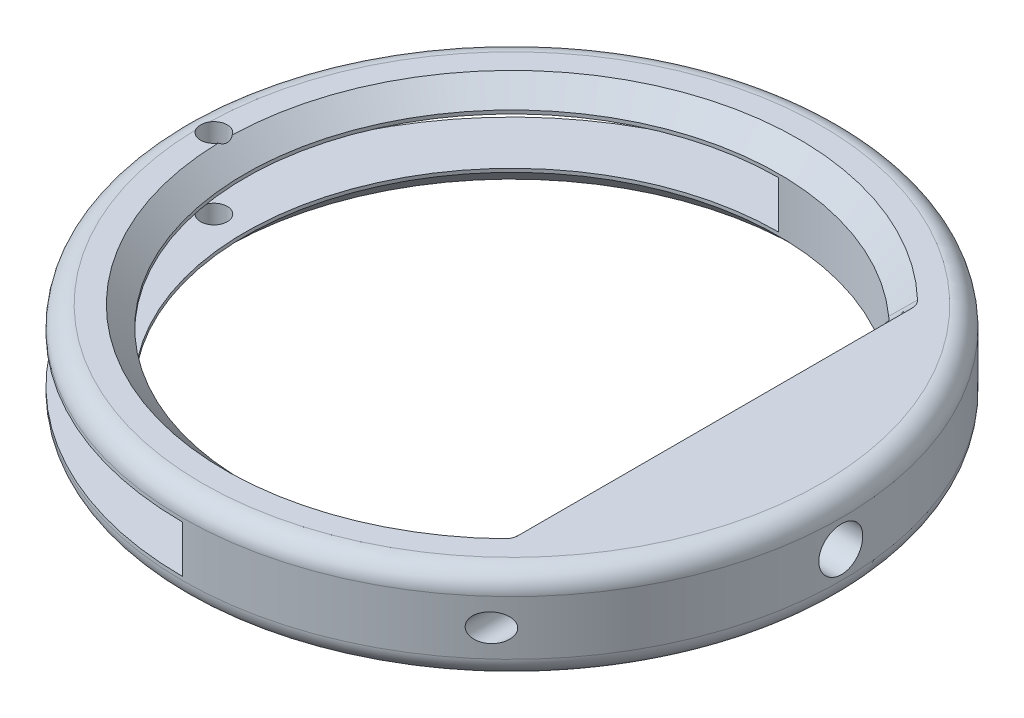
SolidWorks part; units mm, degrees
ref_plane "Front Plane" through (0, 0, 0) normal (0, 0, 1) x (1, 0, 0)
ref_plane "Top Plane" through (0, 0, 0) normal (0, 1, 0) x (1, 0, 0)
ref_plane "Right Plane" through (0, 0, 0) normal (1, 0, 0) x (0, 0, -1)
sketch "Sketch1" plane through (0, 0, 0) normal (0, 1, 0) x (1, 0, 0)
  circle A0 centre (0, 0) radius 17
  circle A1 centre (0, 0) radius 21
  dimension "D1" = 34
  dimension "D2" = 4
extrude "Boss-Extrude1" add sketch "Sketch1" along normal blind 6
sketch "Sketch2" plane through (0, 0, 0) normal (1, 0, 0) x (0, 0, -1)
  line L0 (21, 3) -> (-21, 3) construction
  line L1 (21, 0) -> (21, 6) construction
  line L2 (-21, 6) -> (-21, 0) construction
  line L4 (21, 4.5) -> (-21, 4.5)
  line L5 (21, 4.5) -> (21, 1.5)
  line L6 (21, 1.5) -> (-21, 1.5)
  line L7 (-21, 4.5) -> (-21, 1.5)
  dimension "D1" = 1.5
  dimension "D2" = 3
extrude "Cut-Extrude1" cut sketch "Sketch2" against normal blind 25.812
ref_plane "Plane1" through (17, 0, 0) normal (-1, 0, 0) x (0, 0, 1)
sketch "Sketch3" plane through (17, 0, 0) normal (-1, 0, 0) x (0, 0, 1)
  line L0 (-17, 0) -> (17, 0) construction
  line L1 (17, 0) -> (-17, 0)
  line L2 (17, 0) -> (17, 6)
  line L3 (17, 6) -> (-17, 6)
  line L4 (-17, 0) -> (-17, 6)
  line L5 (-21, 0) -> (21, 0) construction
  line L6 (17, 6) -> (-17, 6) construction
  line L7 (16.8602, 4.3201) -> (-16.6398, 4.3201) construction
  line L8 (-16.4907, 4.3201) -> (16.7109, 4.3201)
  line L9 (-16.4907, 4.3201) -> (-16.4907, 1.4801)
  line L10 (-16.4907, 1.4801) -> (16.7109, 1.4801)
  line L11 (16.7109, 4.3201) -> (16.7109, 1.4801)
  line L12 (-16.6398, 1.4801) -> (16.8602, 1.4801) construction
extrude "Boss-Extrude2" add sketch "Sketch3" along normal blind 5.334
sketch "Sketch4" plane through (0, 6, 0) normal (0, 1, 0) x (1, 0, 0)
  circle A0 centre (0, 0) radius 21
  circle A1 centre (0, 0) radius 24.0416
extrude "Cut-Extrude2" cut sketch "Sketch4" against normal blind 19.05
ref_plane "Plane2" through (21, 0, 0) normal (1, 0, 0) x (0, 0, -1)
sketch "Sketch5" plane through (21, 0, 0) normal (1, 0, 0) x (0, 0, -1)
  line L0 (0, 0) -> (0, 6) construction
  line L1 (-21, 0) -> (21, 0) construction
  line L2 (-12.3655, 6) -> (12.3655, 6) construction
  circle A1 centre (0, 3) radius 1.4
  dimension "D1" = 2.8
extrude "Cut-Extrude3" cut sketch "Sketch5" against normal blind 19.05
chamfer "Chamfer1" distance 1.2794 angle 45 2 edges at (11.666, 6, 0) (11.666, 0, 0)
chamfer "Chamfer2" distance 1.2794 angle 45 2 edges at (-17, 0, 0) (-17, 6, 0)
fillet "Fillet2" radius 1.27 2 edges at (0, 0, 21) (0, 6, 21)
sketch "Sketch8" plane through (0, 6, 0) normal (0, 1, 0) x (1, 0, 0)
  circle A0 centre (-18.9931, 0) radius 0.85
  dimension "D1" = 1.7
extrude "Cut-Extrude7" cut sketch "Sketch8" against normal blind 15.494
fillet "Fillet3" radius 1.27 4 edges
sketch "Sketch9" plane through (0, 0, 0) normal (0, 0, 1) x (1, 0, 0)
  line L0 (20.9846, 1.27) -> (21, 4.73) construction
  line L1 (21, 1.27) -> (-21, 1.27) construction
  line L2 (14.1576, 3) -> (20.9923, 3)
  circle A0 centre (14.1576, 3) radius 0.875
  dimension "D1" = 1.75
extrude "Cut-Extrude8" cut sketch "Sketch9" against normal blind 28.194 and the other way blind 19.812 contours A0
sketch "Sketch10" plane through (0, 4.5, 0) normal (0, -1, 0) x (-1, 0, 0)
  line L0 (18.1431, 0) -> (16.3955, 0) construction
  arc A0 (18.2738, 0.4528) -> (18.2738, -0.4528) centre (18.9931, 0) ccw construction
